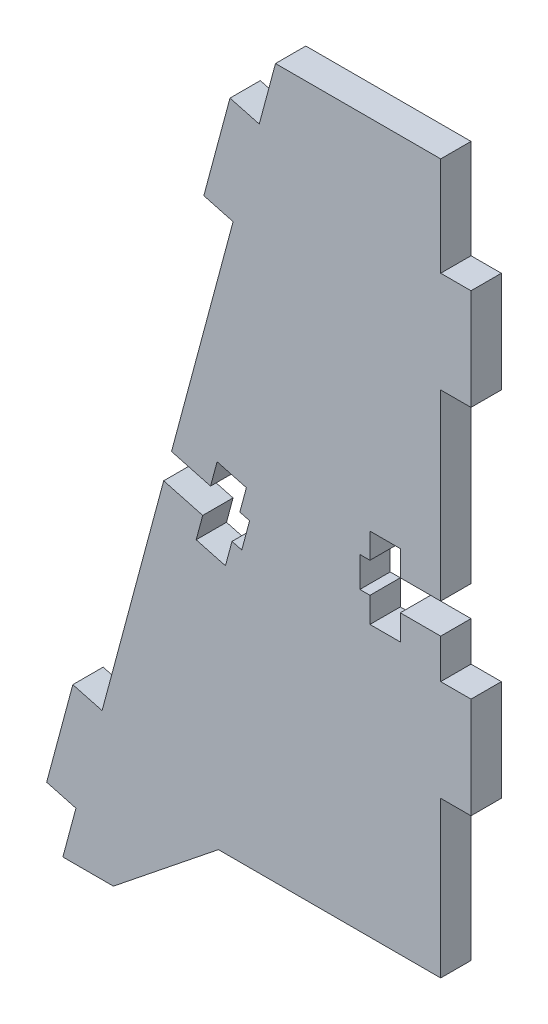
SolidWorks part; units mm, degrees
material "Balsa"
ref_plane "Alzado" through (0, 0, 0) normal (0, 0, 1) x (1, 0, 0)
ref_plane "Planta" through (0, 0, 0) normal (0, 1, 0) x (1, 0, 0)
ref_plane "Vista lateral" through (0, 0, 0) normal (1, 0, 0) x (0, 0, -1)
sketch "Croquis1" plane through (0, 0, 0) normal (0, 0, 1) x (1, 0, 0)
  line L8 (484.8557, 82.973) -> (491.2152, 82.973)
  line L11 (480.6618, 67.3211) -> (477.764, 68.0975)
  line L12 (480.3522, 77.7568) -> (483.25, 76.9803)
  line L13 (465.1089, 9.2769) -> (462.2111, 10.0533)
  line L14 (464.7993, 19.7126) -> (467.6971, 18.9361)
  line L15 (483.25, 76.9803) -> (484.8557, 82.973)
  line L20 (494.8557, 12.7731) -> (479.2056, 12.7731)
  line L21 (465.1089, 9.2769) -> (463.8148, 4.4472)
  line L22 (463.8148, 4.4472) -> (468.8148, 4.4472)
  line L23 (468.8148, 4.4472) -> (479.2056, 12.7731)
  line L25 (494.8557, 12.7731) -> (501.2056, 12.7731)
  line L59 (501.2056, 12.7731) -> (501.2056, 28.1731)
  line L60 (501.2056, 28.1731) -> (504.2056, 28.1731)
  line L61 (504.2056, 28.1731) -> (504.2056, 38.1731)
  line L62 (504.2056, 38.1731) -> (501.2056, 38.1731)
  line L63 (501.2056, 38.1731) -> (501.2056, 42.0731)
  line L64 (501.2056, 63.1731) -> (504.2056, 63.1731)
  line L65 (504.2056, 63.1731) -> (504.2056, 73.1731)
  line L66 (504.2056, 73.1731) -> (501.2056, 73.1731)
  line L67 (501.2056, 73.1731) -> (501.2056, 82.973)
  line L68 (501.2056, 82.973) -> (491.2152, 82.973)
  line L69 (501.2056, 43.5731) -> (488.6228, 43.5731) construction
  line L70 (501.2056, 45.0731) -> (497.2056, 45.0731)
  line L72 (501.2056, 42.0731) -> (497.2056, 42.0731)
  line L73 (493.2056, 45.0731) -> (493.2056, 42.0731)
  line L74 (497.2056, 47.5731) -> (494.2056, 47.5731)
  line L75 (497.2056, 47.5731) -> (497.2056, 45.0731)
  line L76 (497.2056, 39.5731) -> (494.2056, 39.5731)
  line L77 (494.2056, 47.5731) -> (494.2056, 45.0731)
  line L78 (501.2056, 45.0731) -> (501.2056, 63.1731)
  line L79 (497.2056, 42.0731) -> (497.2056, 39.5731)
  line L80 (494.2056, 45.0731) -> (493.2056, 45.0731)
  line L81 (494.2056, 42.0731) -> (493.2056, 42.0731)
  line L82 (494.2056, 42.0731) -> (494.2056, 39.5731)
  line L83 (467.6971, 18.9361) -> (473.791, 41.6789)
  line L84 (474.1792, 43.1277) -> (490.5842, 38.732) construction
  line L85 (473.791, 41.6789) -> (477.6547, 40.6436)
  line L86 (477.6547, 40.6436) -> (477.0076, 38.2288)
  line L87 (477.0076, 38.2288) -> (479.9054, 37.4523)
  line L88 (479.9054, 37.4523) -> (480.5525, 39.8671)
  line L89 (480.5525, 39.8671) -> (481.5184, 39.6083)
  line L90 (481.5184, 39.6083) -> (482.2948, 42.5061)
  line L91 (481.3289, 42.7649) -> (482.2948, 42.5061)
  line L92 (478.4311, 43.5414) -> (479.0782, 45.9562)
  line L93 (479.0782, 45.9562) -> (481.976, 45.1797)
  line L94 (481.976, 45.1797) -> (481.3289, 42.7649)
  line L95 (474.5674, 44.5766) -> (478.4311, 43.5414)
  line L96 (474.5674, 44.5766) -> (480.6618, 67.3211)
  line L116 (480.3522, 77.7568) -> (477.764, 68.0975)
  line L117 (464.7993, 19.7126) -> (462.2111, 10.0533)
  point P43 (481.9066, 41.0572)
  dimension "D1" = 70.1999
  dimension "D2" = 25
  dimension "D3" = 10
  dimension "D4" = 3
  dimension "D5" = 3
  dimension "D6" = 3
  dimension "D7" = 10
  dimension "D8" = 3
  dimension "D9" = 15.4
  dimension "D10" = 22
  dimension "D11" = 3
  dimension "D12" = 1.5
  dimension "D13" = 4
  dimension "D14" = 8
  dimension "D15" = 3
  dimension "D16" = 1
  dimension "D17" = 5.4
  dimension "D18" = 8
  dimension "D19" = 6.163
  dimension "D20" = 54.548
  dimension "D21" = 25.045
  dimension "D22" = 1.5
  dimension "D23" = 4
  dimension "D24" = 1.5
  dimension "D25" = 1
  dimension "D26" = 3
  dimension "D27" = 4
extrude "Saliente-Extruir1" add sketch "Croquis1" along normal mid plane 3
